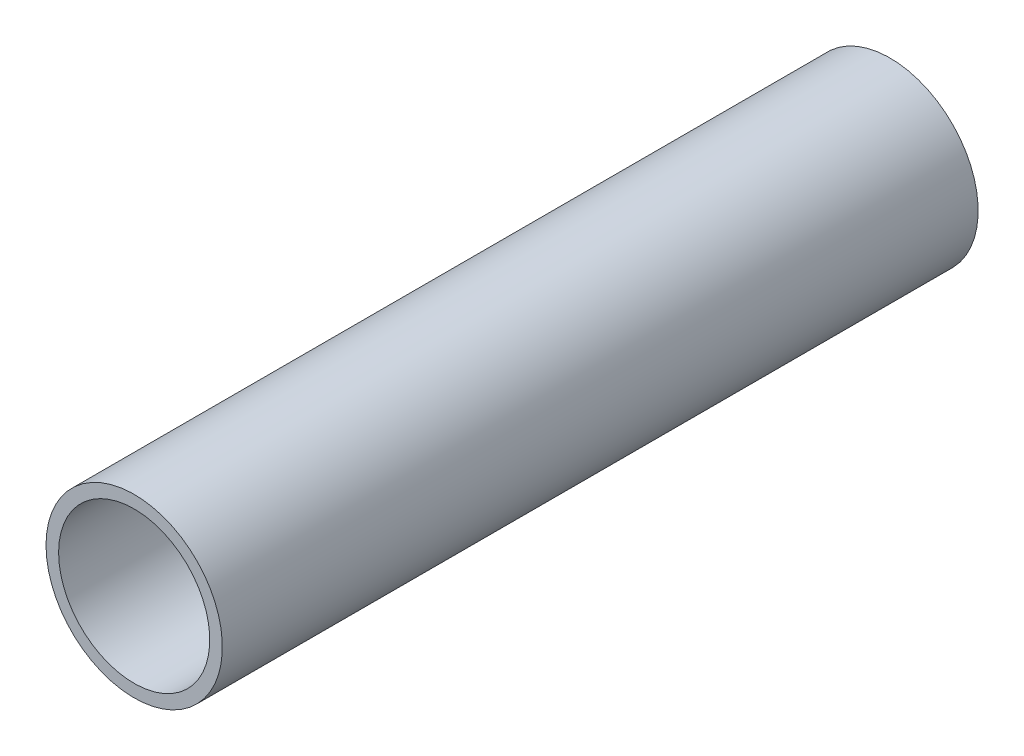
SolidWorks part; units mm, degrees
material "Fibre de verre A"
ref_plane "Plan de face" through (0, 0, 0) normal (0, 0, 1) x (1, 0, 0)
ref_plane "Plan de dessus" through (0, 0, 0) normal (0, 1, 0) x (1, 0, 0)
ref_plane "Plan de droite" through (0, 0, 0) normal (1, 0, 0) x (0, 0, -1)
sketch "Esquisse1" plane through (0, 0, 0) normal (0, 0, 1) x (1, 0, 0)
  circle A0 centre (0, 0) radius 7
  circle A1 centre (0, 0) radius 6
  dimension "D1" = 12
  dimension "D2" = 14
extrude "Boss.-Extru.1" add sketch "Esquisse1" along normal blind 60
